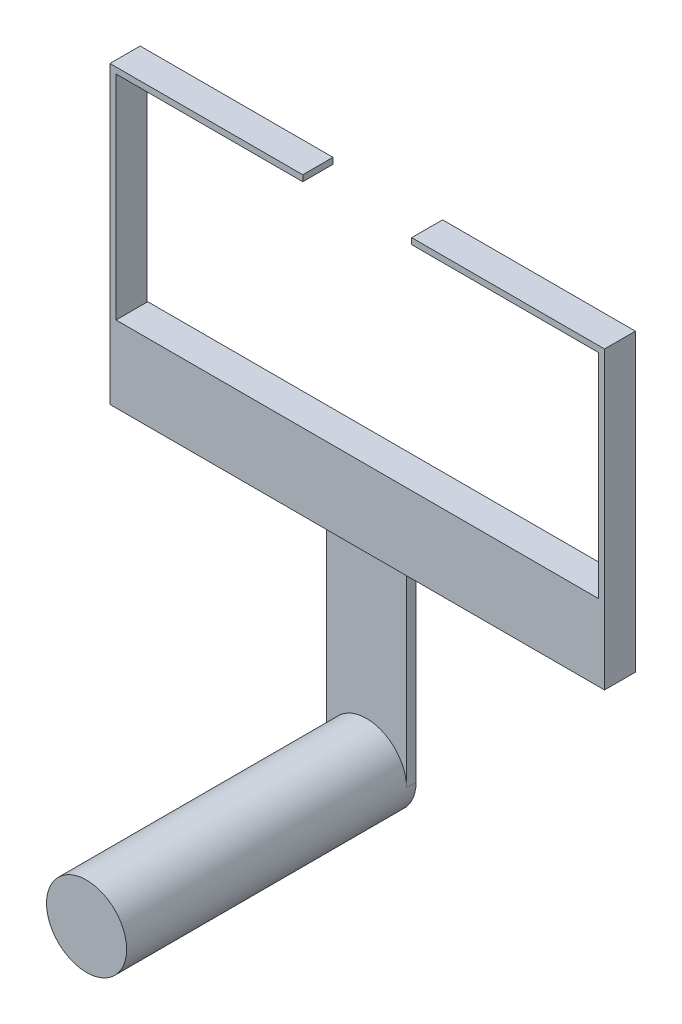
SolidWorks part; units mm, degrees
ref_plane "Front Plane" through (0, 0, 0) normal (0, 0, 1) x (1, 0, 0)
ref_plane "Top Plane" through (0, 0, 0) normal (0, 1, 0) x (1, 0, 0)
ref_plane "Right Plane" through (0, 0, 0) normal (1, 0, 0) x (0, 0, -1)
sketch "Sketch1" plane through (0, 0, 0) normal (0, 0, 1) x (1, 0, 0)
  circle A0 centre (0, 0) radius 5.2704
  dimension "D1" = 10.5408
extrude "Feature A" add sketch "Sketch1" against normal blind 38.1
sketch "Sketch2" plane through (0, 0, -38.1) normal (0, 0, -1) x (-1, 0, 0)
  line L0 (-5.2704, 0) -> (5.2704, 0) construction
  line L2 (-5.2704, 0) -> (5.2704, 0)
  line L3 (-5.2704, 0) -> (-5.2704, 25.4)
  line L4 (-5.2704, 25.4) -> (5.2704, 25.4)
  line L5 (5.2704, 0) -> (5.2704, 25.4)
  circle A0 centre (0, 0) radius 5.2704 construction
extrude "Feature B" add sketch "Sketch2" against normal blind 1.2468
sketch "Sketch5" plane through (0, 25.4, 0) normal (0, 1, 0) x (1, 0, 0)
  line L0 (0, 0) -> (0, 41.7447) construction
  line L1 (-5.2704, 37.4766) -> (8.9227, 37.4766) construction
  line L2 (-5.2704, 36.8532) -> (-5.2704, 38.1) construction
  line L4 (31.75, 35.6271) -> (-31.75, 35.6271)
  line L5 (31.75, 35.6271) -> (31.75, 39.8007)
  line L6 (31.75, 39.8007) -> (-31.75, 39.8007)
  line L7 (-31.75, 35.6271) -> (-31.75, 39.8007)
  line L8 (31.75, 35.6271) -> (-31.75, 39.8007) construction
  line L9 (31.75, 39.8007) -> (-31.75, 35.6271) construction
  point P7 (0, 37.7139)
  dimension "D1" = 63.5
extrude "Feature C" add sketch "Sketch5" along normal blind 10.0278
sketch "Sketch6" plane through (0, 0, -35.6271) normal (0, 0, 1) x (1, 0, 0)
  line L1 (-31.75, 25.4) -> (-32.5502, 25.4)
  line L2 (-31.75, 25.4) -> (-31.75, 63.4746)
  line L3 (-31.75, 63.4746) -> (-32.5502, 63.4746)
  line L4 (-32.5502, 25.4) -> (-32.5502, 63.4746)
  line L5 (31.75, 25.4) -> (32.5502, 25.4)
  line L6 (31.75, 25.4) -> (31.75, 63.4746)
  line L7 (31.75, 63.4746) -> (32.5502, 63.4746)
  line L8 (32.5502, 25.4) -> (32.5502, 63.4746)
  dimension "D1" = 38.0746
  dimension "D3" = 0.8002
  dimension "D4" = 38.0746
extrude "Feature D" add sketch "Sketch6" against normal blind 4.064
sketch "Sketch7" plane through (0, 63.4746, 0) normal (0, 1, 0) x (1, 0, 0)
  line L1 (-32.5502, 35.6271) -> (-7.1705, 35.6271)
  line L2 (-32.5502, 35.6271) -> (-32.5502, 39.6028)
  line L3 (-32.5502, 39.6028) -> (-7.1705, 39.6028)
  line L4 (-7.1705, 35.6271) -> (-7.1705, 39.6028)
  line L5 (32.5502, 39.6911) -> (7.1705, 39.6911)
  line L6 (32.5502, 39.6911) -> (32.5502, 35.6271)
  line L7 (32.5502, 35.6271) -> (7.1705, 35.6271)
  line L8 (7.1705, 39.6911) -> (7.1705, 35.6271)
  dimension "D2" = 25.3797
extrude "Feature E" add sketch "Sketch7" along normal blind 0.8002
equation "\"F\"= 650'Force "
equation "\"SF\"= 4'Safety Factor"
equation "\"Emod\"= 16505294'Young's Modulus "
equation "\"Sy\"= 127633'Yield Strength"
equation "\"AllowStress\"= \"Sy\" / \"SF\""
equation "\"FeatAL\"= 1.5in'Length of Feature A"
equation "\"diaFeatA\"= ( ( \"F\" * \"FeatAL\" * \"SF\" * 32 ) / ( \"AllowStress\" * pi ) ) ^ 1 / 3in'Diameter of Feature A"
equation "\"WidthB\"= \"diaFeatA\""
equation "\"AreaB\"= ( \"F\" * \"SF\" ) / ( \"Sy\" )'Area of Feature B "
equation "\"ThickB\"= \"AreaB\" / \"WidthB\"'Thickness of B "
equation "\"LengthC\"= 2.50in'Length of C"
equation "\"AreaC\"= ( 2 * \"F\" * 4 ) / ( \"Sy\" )'Area of C "
equation "\"HeightC\"= ( 12 * \"I\" / \"LengthC\" ) ^ ( 1 / 3 )'Height of C"
equation "\"Height D\"= 1.499'Height of D "
equation "\"Area D\"= ( \"F\" * \"Height D\" * \"SF\" ) / ( \"Emod\" * \"maxdefl\" )'Area D"
equation "\"LengthD\"= ( \"Area D\" / \"Height D\" )"
equation "\"LengthE\"= 0.9992in"
equation "\"AreaE\"= ( \"F\" * \"SF\" * \"LengthE\" ) / ( \"Emod\" * \"maxdefl\" )"
equation "\"HeightE\"= ( \"AreaE\" / \"LengthE\" )"
equation "\"I\"= ( ( 5 * 2 * \"F\" * ( \"LengthC\" ) ^ 3 * \"SF\" ) / ( 384 * \"Emod\" * \"maxdefl\" ) )'Moment of Inertia "
equation "\"maxdefl\"= 0.005in'maximum deflection"
equation "\"D1@Sketch1\"=\"diaFeatA\""
equation "\"D1@Feature B\"=\"ThickB\""
equation "\"D1@Sketch5\"=\"LengthC\""
equation "\"D1@Feature C\"=\"HeightC\""
equation "\"D1@Sketch6\"=\"Height D\""
equation "\"D4@Sketch6\"=\"Height D\""
equation "\"D2@Sketch6\"=\"LengthD\""
equation "\"D3@Sketch6\"=\"LengthD\""
equation "\"D1@Sketch7\"=\"LengthE\""
equation "\"D2@Sketch7\"=\"LengthE\""
equation "\"D1@Feature E\"=\"HeightE\""
equation "\"assumlengthb\"= 1.00in'assumption of distance betw A B"
equation "\"D1@Sketch2\"=\"assumlengthb\""
